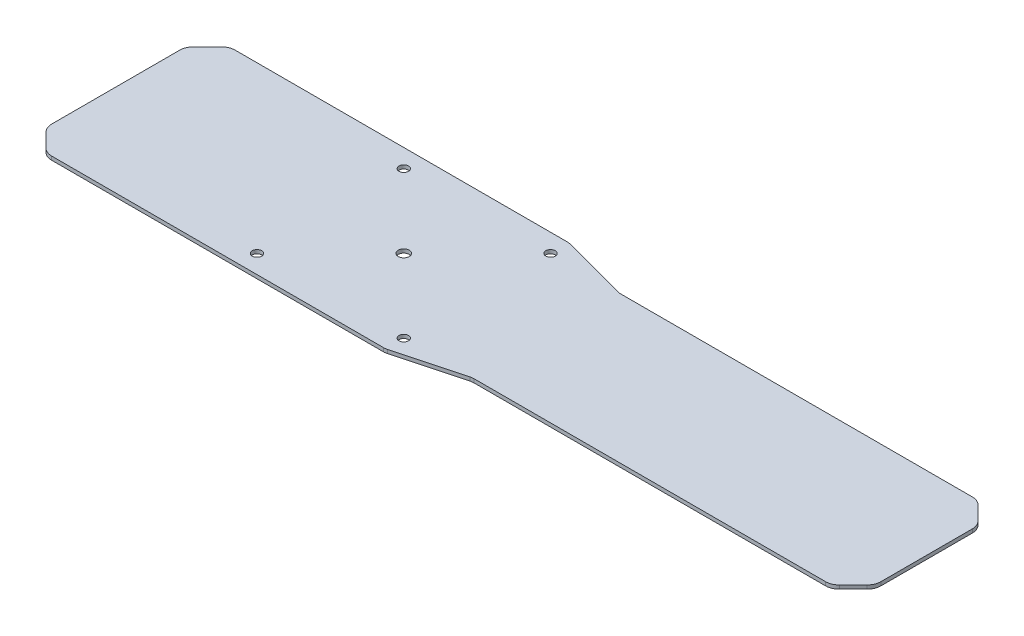
SolidWorks part; units mm, degrees
material "1060 Alloy"
ref_plane "Front Plane" through (0, 0, 0) normal (0, 0, 1) x (1, 0, 0)
ref_plane "Top Plane" through (0, 0, 0) normal (0, 1, 0) x (1, 0, 0)
ref_plane "Right Plane" through (0, 0, 0) normal (1, 0, 0) x (0, 0, -1)
sketch "Sketch1" plane through (0, 0, 0) normal (0, 1, 0) x (1, 0, 0)
  line L0 (40, -50) -> (77.3205, -40)
  line L1 (-40, 50) -> (40, 50)
  line L2 (-40, 50) -> (-40, -50) construction
  line L3 (-40, -50) -> (40, -50)
  line L4 (40, 50) -> (40, -50) construction
  line L5 (-40, 50) -> (40, -50) construction
  line L6 (-40, -50) -> (40, 50) construction
  line L7 (-40, 50) -> (-157, 50)
  line L8 (-40, 50) -> (-40, -50) construction
  line L9 (-40, -50) -> (-157, -50)
  line L10 (-157, 50) -> (-157, -50)
  line L12 (40, 50) -> (40, -50) construction
  line L14 (40, 50) -> (77.3205, 40)
  line L16 (77.3205, 40) -> (285, 40)
  line L17 (77.3205, 40) -> (77.3205, -40) construction
  line L18 (77.3205, -40) -> (285, -40)
  line L19 (285, 40) -> (285, -40)
  point P0 (0, 0)
  point P11 (250, 0)
  dimension "D1" = 80
  dimension "D2" = 100
  dimension "D5" = 250
  dimension "D4" = 75
  dimension "D6" = 75
  dimension "D7" = 80
  dimension "D8" = 35
  dimension "D3" = 117
extrude "Boss-Extrude2" add sketch "Sketch1" along normal blind 2
chamfer "Chamfer2" distance 12 angle 45 4 edges at (-157, 1, 50) (-157, 1, -50) (285, 1, -40) (285, 1, 40)
fillet "Fillet1" radius 7.5 12 edges at (-145, 1, -50) (-157, 1, -38) (-157, 1, 38) (-145, 1, 50) (273, 1, 40) (285, 1, 28) (285, 1, -28) (273, 1, -40) (40, 1, 50) (77.3205, 1, 40) (77.3205, 1, -40) (40, 1, -50)
sketch "Sketch2" plane through (0, 2, 0) normal (0, 1, 0) x (1, 0, 0)
  line L0 (0, 50) -> (0, -50) construction
  line L1 (39.0126, 50) -> (-141.8934, 50) construction
  line L2 (-141.8934, -50) -> (39.0126, -50) construction
  line L3 (-157, 0) -> (285, 0) construction
  line L4 (-157, 34.8934) -> (-157, -34.8934) construction
  line L5 (285, -24.8934) -> (285, 24.8934) construction
  circle A0 centre (-40, 40) radius 2.575
  circle A1 centre (40, 40) radius 2.575
  circle A2 centre (40, -40) radius 2.575
  circle A3 centre (-40, -40) radius 2.575
  circle A5 centre (0, 0) radius 3
  dimension "D3" = 5.15
  dimension "D6" = 6
  dimension "D1" = 40
  dimension "D2" = 40
extrude "Cut-Extrude1" cut sketch "Sketch2" against normal through all
equation "\"Elevator Guide Rod Distance\"= 80mm"
equation "\"Extra Spacing\"= 20mm"
equation "\"Plate Thickness\"= 2mm"
equation "\"D1@Sketch1\"=\"Elevator Guide Rod Distance\""
equation "\"D2@Sketch1\"=\"Elevator Guide Rod Distance\"+\"Extra Spacing\""
equation "\"Elevator Servo Offset\"= 75mm"
equation "\"Servo Width\"= 42mm"
equation "\"Pivot Point End Offset\"= 35mm"
equation "\"Origin Pivot Distance\"= 250mm"
equation "\"D5@Sketch1\"=\"Origin Pivot Distance\""
equation "\"Narrow Section Width\"= 80mm"
equation "\"D7@Sketch1\"=\"Narrow Section Width\""
equation "\"D8@Sketch1\"=\"Pivot Point End Offset\""
equation "\"D1@Sketch2\"=\"Elevator Guide Rod Distance\"/2"
equation "\"D2@Sketch2\"=\"Elevator Guide Rod Distance\"/2"
equation "\"Guide Rod Diameter\"= 5mm"
equation "\"D3@Sketch2\"=\"Guide Rod Diameter\"+.15"
equation "\"Servo Hole X-Offset\"= 15.5mm"
equation "\"Servo Hole Y-Offset\"= 15.5mm"
equation "\"D1\"= \"Servo Width\" / 2 + \"Extra Spacing\""
equation "\"Servo Shaft Diameter\"= 22.5mm"
equation "\"Elevator Screw Lift Diameter\"= 6mm"
equation "\"D6@Sketch2\"=\"Elevator Screw Lift Diameter\""
equation "\"D3@Sketch1\"=\"Servo Width\" + \"Extra Spacing\" * 2 + 35"
equation "\"D1@Boss-Extrude2\"=\"Plate Thickness\""
